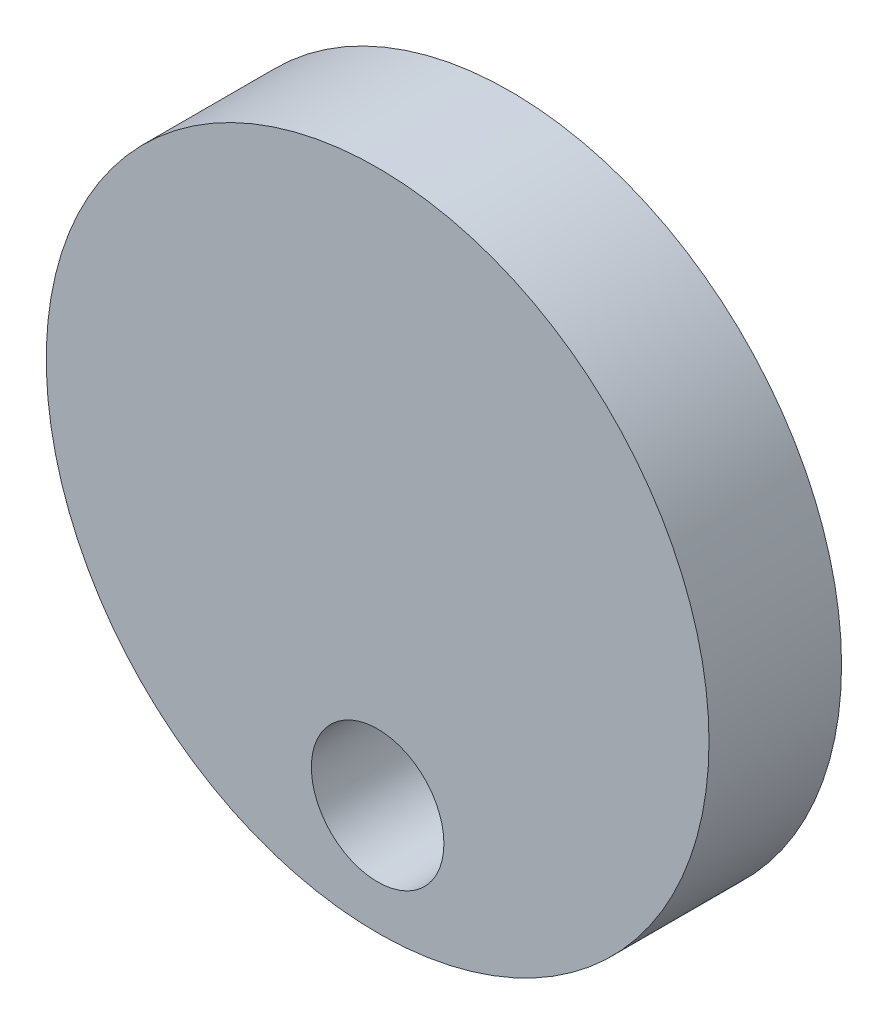
SolidWorks part; units mm, degrees
ref_plane "Front Plane" through (0, 0, 0) normal (0, 0, 1) x (1, 0, 0)
ref_plane "Top Plane" through (0, 0, 0) normal (0, 1, 0) x (1, 0, 0)
ref_plane "Right Plane" through (0, 0, 0) normal (1, 0, 0) x (0, 0, -1)
sketch "Sketch2" plane through (0, 0, 0) normal (0, 0, 1) x (1, 0, 0)
  line L0 (0, -15) -> (50000, -15) construction
  line L1 (0, -7) -> (50000, -7) construction
  line L2 (0, -13) -> (50000, -13) construction
  circle A0 centre (0, 0) radius 15
  circle A1 centre (0, -10) radius 3
  dimension "D2" = 6
  dimension "D4" = 30
  dimension "D3" = 7
  dimension "D1" = 2
extrude "Boss-Extrude1" add sketch "Sketch2" along normal blind 6
equation "\"translationDistance\"= 7"
equation "\"D3@Sketch2\"=\"translationDistance\""
